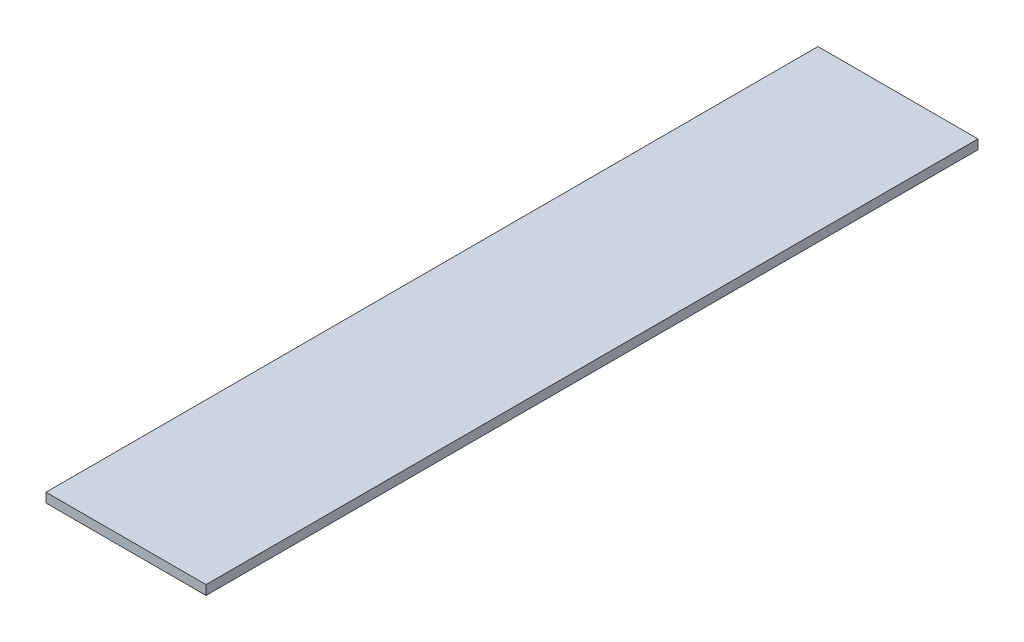
SolidWorks part; units mm, degrees
material "Сосна"
ref_plane "Спереди" through (0, 0, 0) normal (0, 0, 1) x (1, 0, 0)
ref_plane "Сверху" through (0, 0, 0) normal (0, 1, 0) x (1, 0, 0)
ref_plane "Справа" through (0, 0, 0) normal (1, 0, 0) x (0, 0, -1)
sketch "Эскиз1" plane through (0, 0, 0) normal (0, 0, 1) x (1, 0, 0)
  line L1 (0, 0) -> (170, 0)
  line L2 (0, 0) -> (0, 10)
  line L3 (0, 10) -> (170, 10)
  line L4 (170, 0) -> (170, 10)
  dimension "D1" = 10
  dimension "D2" = 170
extrude "Бобышка-Вытянуть1" add sketch "Эскиз1" against normal blind 820
